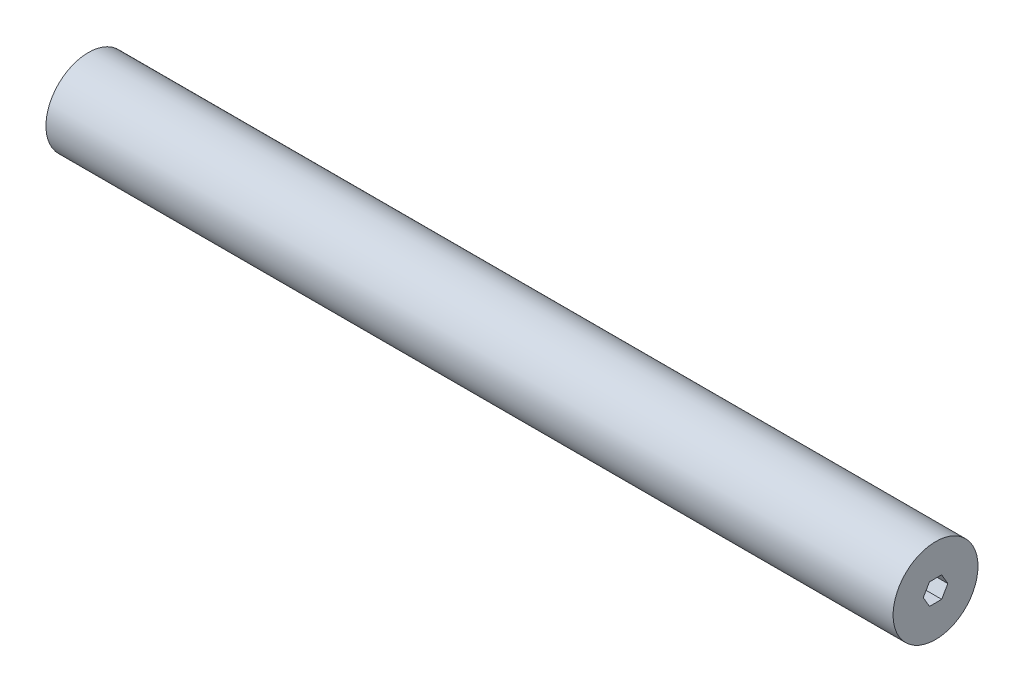
SolidWorks part; units mm, degrees
material "PVC Rígido"
ref_plane "Alzado" through (0, 0, 0) normal (0, 0, 1) x (1, 0, 0)
ref_plane "Planta" through (0, 0, 0) normal (0, 1, 0) x (1, 0, 0)
ref_plane "Vista lateral" through (0, 0, 0) normal (1, 0, 0) x (0, 0, -1)
sketch "Croquis1" plane through (0, 0, 0) normal (1, 0, 0) x (0, 0, -1)
  line L1 (-7.3323, 0) -> (-3.6662, -6.35)
  line L2 (-3.6662, -6.35) -> (3.6662, -6.35)
  line L3 (3.6662, -6.35) -> (7.3323, 0)
  line L4 (7.3323, 0) -> (3.6662, 6.35)
  line L5 (3.6662, 6.35) -> (-3.6662, 6.35)
  line L6 (-3.6662, 6.35) -> (-7.3323, 0)
  circle A0 centre (0, 0) radius 25.4
  circle A1 centre (0, 0) radius 6.35 construction
  dimension "D1" = 50.8
  dimension "D2" = 12.7
extrude "Saliente-Extruir1" add sketch "Croquis1" along normal blind 507
